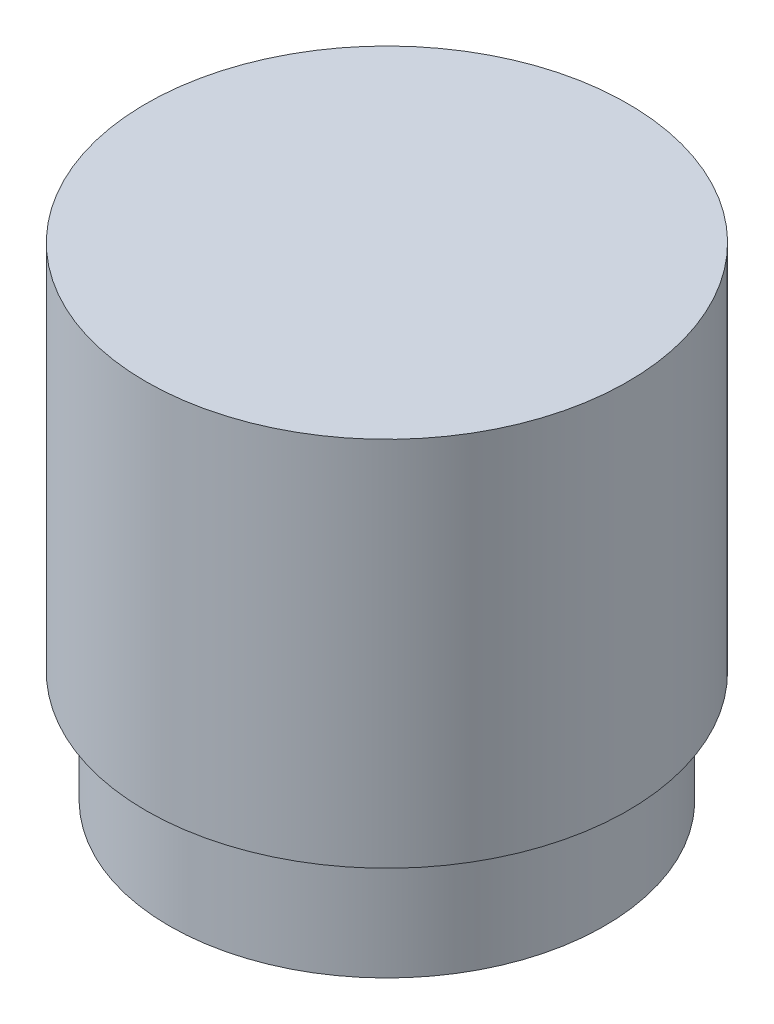
SolidWorks part; units mm, degrees
other "DetailItem1"
material "Brass"
ref_plane "Front Plane" through (0, 0, 0) normal (0, 0, 1) x (1, 0, 0)
ref_plane "Top Plane" through (0, 0, 0) normal (0, 1, 0) x (1, 0, 0)
ref_plane "Right Plane" through (0, 0, 0) normal (1, 0, 0) x (0, 0, -1)
sketch "Sketch1" plane through (0, 0, 0) normal (0, 1, 0) x (1, 0, 0)
  circle A0 centre (0, 0) radius 1.875
  dimension "D1" = 3.75
extrude "Boss-Extrude1" add sketch "Sketch1" along normal blind 0.96
sketch "Sketch2" plane through (0, 0.96, 0) normal (0, 1, 0) x (1, 0, 0)
  circle A0 centre (0, 0) radius 2.075
  dimension "D1" = 4.15
extrude "Boss-Extrude2" add sketch "Sketch2" along normal blind 3.2
